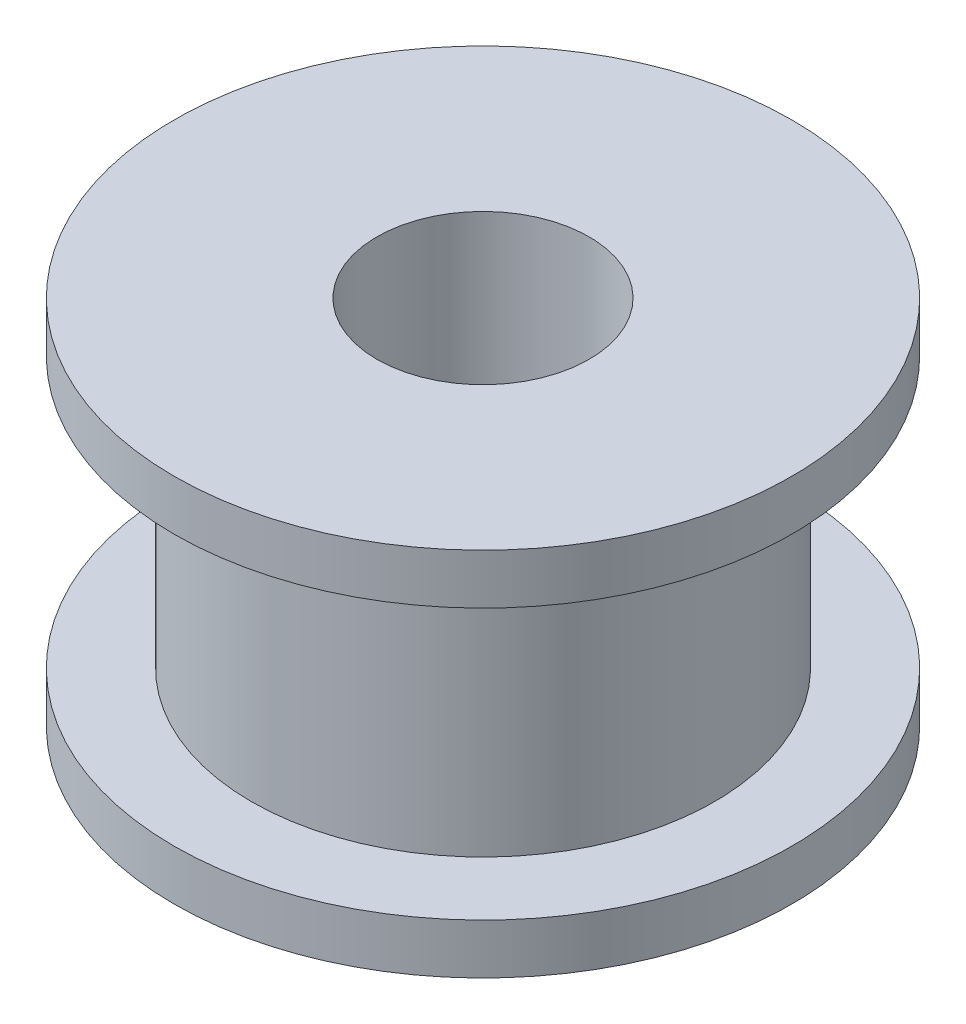
SolidWorks part; units mm, degrees
ref_plane "Front Plane" through (0, 0, 0) normal (0, 0, 1) x (1, 0, 0)
ref_plane "Top Plane" through (0, 0, 0) normal (0, 1, 0) x (1, 0, 0)
ref_plane "Right Plane" through (0, 0, 0) normal (1, 0, 0) x (0, 0, -1)
sketch "Sketch1" plane through (0, 0, 0) normal (0, 1, 0) x (1, 0, 0)
  circle A0 centre (0, 0) radius 8
  dimension "D1" = 16
extrude "Boss-Extrude1" add sketch "Sketch1" along normal blind 1.3
sketch "Sketch2" plane through (0, 1.3, 0) normal (0, 1, 0) x (1, 0, 0)
  circle A0 centre (0, 0) radius 6
  dimension "D1" = 12
extrude "Boss-Extrude2" add sketch "Sketch2" along normal blind 7
sketch "Sketch3" plane through (0, 8.3, 0) normal (0, 1, 0) x (1, 0, 0)
  circle A0 centre (0, 0) radius 8 construction
  circle A1 centre (0, 0) radius 8
extrude "Boss-Extrude3" add sketch "Sketch3" along normal blind 1.3
sketch "Sketch4" plane through (0, 9.6, 0) normal (0, 1, 0) x (1, 0, 0)
  circle A0 centre (0, 0) radius 2.75
  dimension "D1" = 5.5
extrude "Cut-Extrude1" cut sketch "Sketch4" against normal blind 8.6
